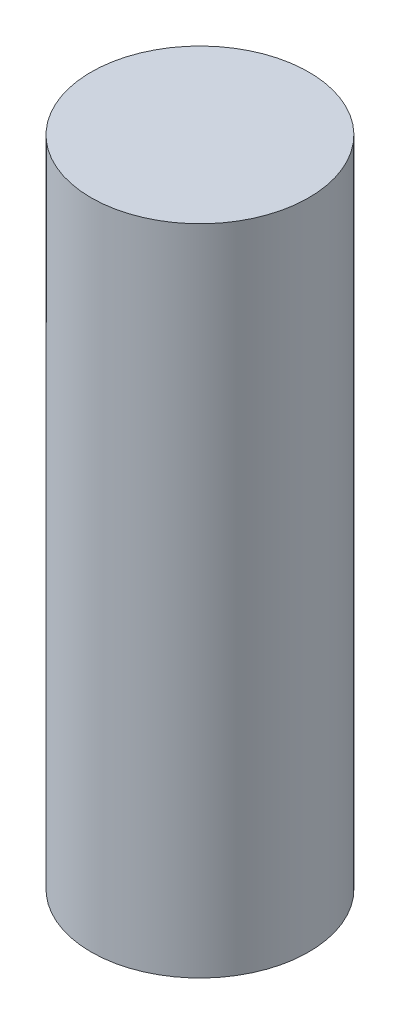
SolidWorks part; units mm, degrees
ref_plane "Front Plane" through (0, 0, 0) normal (0, 0, 1) x (1, 0, 0)
ref_plane "Top Plane" through (0, 0, 0) normal (0, 1, 0) x (1, 0, 0)
ref_plane "Right Plane" through (0, 0, 0) normal (1, 0, 0) x (0, 0, -1)
sketch "Sketch1" plane through (0, 0, 0) normal (0, 1, 0) x (1, 0, 0)
  circle A0 centre (0, 0) radius 63.5
  dimension "D1" = 127
extrude "Boss-Extrude1" add sketch "Sketch1" along normal blind 381
